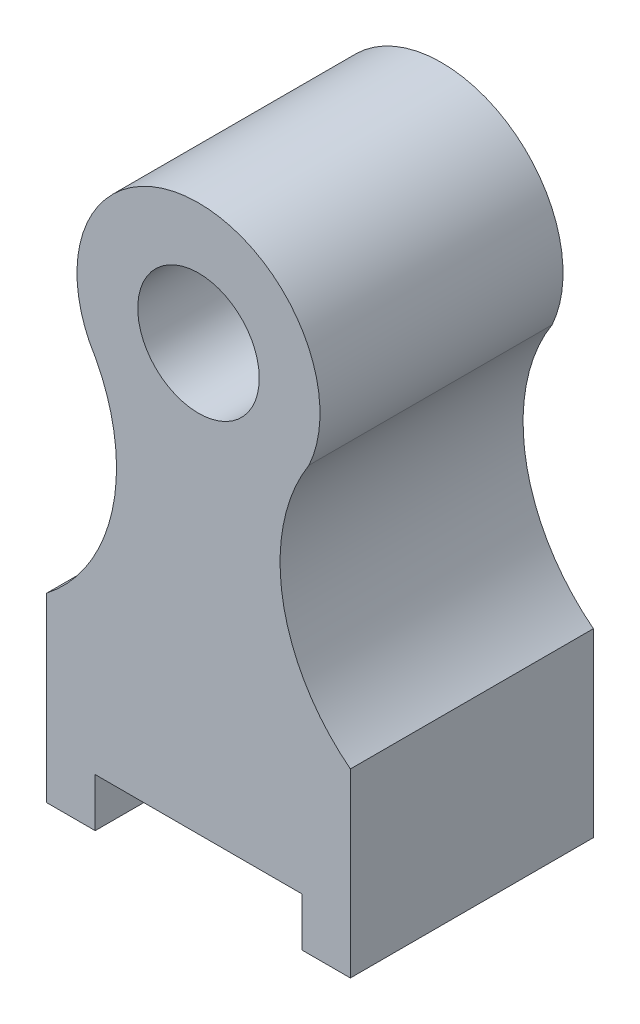
SolidWorks part; units mm, degrees
ref_plane "Front Plane" through (0, 0, 0) normal (0, 0, 1) x (1, 0, 0)
ref_plane "Top Plane" through (0, 0, 0) normal (0, 1, 0) x (1, 0, 0)
ref_plane "Right Plane" through (0, 0, 0) normal (1, 0, 0) x (0, 0, -1)
sketch "Sketch1" plane through (0, 0, 0) normal (0, 0, 1) x (1, 0, 0)
  line L0 (43.18, -198.12) -> (63.5, -198.12)
  line L2 (-63.5, -121.92) -> (-63.5, -198.12)
  line L3 (-63.5, -198.12) -> (-43.18, -198.12)
  line L4 (63.5, -121.92) -> (63.5, -198.12)
  line L14 (-43.18, -198.12) -> (-43.18, -177.8)
  line L15 (-43.18, -177.8) -> (43.18, -177.8)
  line L16 (43.18, -198.12) -> (43.18, -177.8)
  circle A0 centre (0, 0) radius 25.4
  arc A1 (41.8955, -28.7299) -> (-42.6119, -27.6562) centre (0, 0) ccw
  arc A2 (-63.5, -122.2958) -> (-45.7153, -22.1529) centre (-110.4804, -62.3017) ccw
  arc A3 (46.2342, -21.0485) -> (63.5, -122.4354) centre (110.3014, -62.3017) ccw
  circle A4 centre (0, 0) radius 50.8 construction
  point P8 (-110.4804, -62.3017)
  point P13 (0, 0)
  point P16 (0, 0)
  point P19 (-112.961, -60.3307)
  point P20 (0, 0)
  point P21 (111.0186, -62.5238)
  point P22 (110.8548, -62.2516)
  point P23 (110.3014, -62.3017)
  dimension "D1" = 50.8
  dimension "D3" = 152.4
  dimension "D2" = 101.6
  dimension "D4" = 152.4
  dimension "D5" = 198.12
  dimension "D6" = 63.5
  dimension "D7" = 63.5
  dimension "D8" = 76.2
  dimension "D9" = 20.32
  dimension "D10" = 20.32
  dimension "D11" = 20.32
extrude "Boss-Extrude1" add sketch "Sketch1" along normal blind 101.6 contours A3 A1 A2 L2 L3 L14 L15 L16 L0 L4 A0
